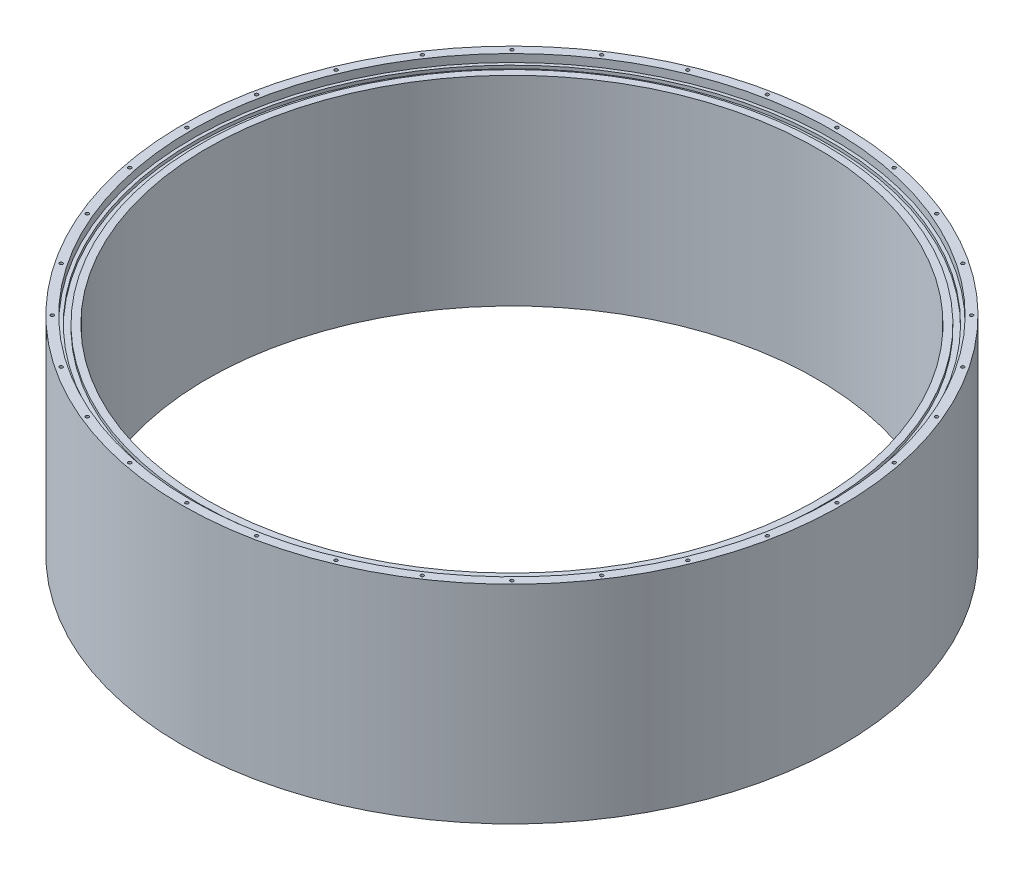
SolidWorks part; units mm, degrees
material "6061-T6"
ref_plane "Front" through (0, 0, 0) normal (0, 0, 1) x (1, 0, 0)
ref_plane "Top" through (0, 0, 0) normal (0, 1, 0) x (1, 0, 0)
ref_plane "Right" through (0, 0, 0) normal (1, 0, 0) x (0, 0, -1)
sketch "Sketch1" plane through (0, 0, 0) normal (0, 0, 1) x (1, 0, 0)
  line L0 (234.95, 74) -> (247, 74)
  line L1 (247, 74) -> (247, 80)
  line L2 (247, 80) -> (254, 80)
  line L3 (254, 80) -> (254, -80)
  line L4 (254, -80) -> (234.95, -80)
  line L5 (234.95, -80) -> (234.95, 74)
  line L6 (0, 80) -> (0, -80) construction
  dimension "D1" = 508
  dimension "D2" = 7
  dimension "D3" = 19.05
  dimension "D4" = 6
  dimension "D5" = 160
revolve "Revolve1" add sketch "Sketch1" angle 360 about L6
sketch "Sketch2" plane through (0, 0, 0) normal (0, 0, 1) x (1, 0, 0)
  line L0 (0, 80) -> (0, -80) construction
  line L1 (254, 80) -> (-254, 80) construction
  line L2 (-254, -80) -> (254, -80) construction
  line L4 (240.3344, 74) -> (244.5, 74)
  line L5 (240.3344, 74) -> (240.3344, 71.587)
  line L6 (240.3344, 71.587) -> (244.5, 71.587)
  line L7 (244.5, 74) -> (244.5, 71.587)
  line L8 (234.95, 74) -> (-234.95, 74) construction
  line L9 (234.95, 74) -> (-234.95, 74) construction
  line L10 (254, -80) -> (254, 80) construction
  line L12 (240.3344, -77.587) -> (244.5, -77.587)
  line L13 (240.3344, -77.587) -> (240.3344, -80)
  line L14 (240.3344, -80) -> (244.5, -80)
  line L15 (244.5, -77.587) -> (244.5, -80)
  dimension "D1" = 9.5
  dimension "D2" = 2.413
  dimension "D3" = 4.1656
revolve "Cut-Revolve1" cut sketch "Sketch2" angle 360 about L0
hole_wizard "M3x0.5 Tapped Hole1" positions "Sketch3" profile "Sketch4" tap size "M3x0.5" standard "ANSI Metric"
sketch "Sketch3" plane through (0, 80, 0) normal (0, 1, 0) x (1, 0, 0)
  point P0 (250.5, 0)
  dimension "D1" = 250.5
sketch "Sketch4" plane through (250.5, 80, 0) normal (1, 0, 0) x (0, 0, 1)
  line L0 (0, 0) -> (0, 10.2511)
  line L1 (0, 10.2511) -> (1.25, 9.5)
  line L2 (1.25, 9.5) -> (1.25, 0)
  line L5 (1.25, 0) -> (0, 0)
  line L10 (0, 10.2511) -> (-1.25, 9.5) construction
  line L11 (0, -6.35) -> (0, 107.95) construction
  dimension "Tap Drill Dia." = 2.5
  dimension "Tap Drill Depth" = 9.5
  dimension "Drill Angle" = 118
cosmetic thread "Hole Thread1" parameters "D1"=8, "D2"=3
pattern_circular "CirPattern1" count 32 over 360 about axis through (0, 0, 0) along (0, 1, 0) of "M3x0.5 Tapped Hole1"
mirror "Mirror1" about plane through (0, 0, 0) normal (0, 1, 0) of "CirPattern1", "M3x0.5 Tapped Hole1"
